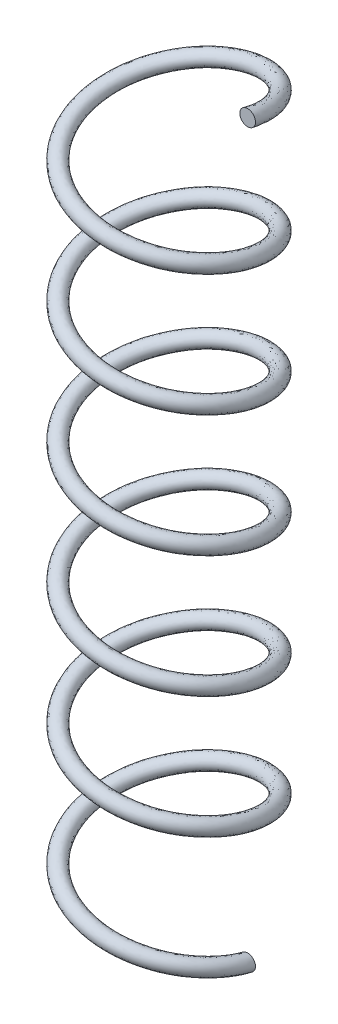
SolidWorks part; units mm, degrees
ref_plane "Front Plane" through (0, 0, 0) normal (0, 0, 1) x (1, 0, 0)
ref_plane "Top Plane" through (0, 0, 0) normal (0, 1, 0) x (1, 0, 0)
ref_plane "Right Plane" through (0, 0, 0) normal (1, 0, 0) x (0, 0, -1)
sketch "Sketch1" plane through (0, 0, 0) normal (1, 0, 0) x (0, 0, -1)
  line L0 (0, 0) -> (0, 19) construction
  dimension "D1" = 19
sketch "Sketch2" plane through (0, 0, 0) normal (0, 1, 0) x (1, 0, 0)
  circle A0 centre (0, 0) radius 2
  dimension "D1" = 4
curve "Helix/Spiral1" pitch 3.1 height 18.6 turns 6
sketch "Sketch3" plane through (0, 0, 0) normal (0, 1, 0) x (1, 0, 0)
  arc A0 (9.9705, 0) -> (5.8804, 2.7912) centre (6.973, 0) cw
sketch "Sketch4" plane through (0, 0, 0) normal (0, 0, 1) x (1, 0, 0)
  circle A0 centre (2, 0) radius 0.2
  spline S0 degree 3 poles (2, 0) (2, 0.0642) (1.8959, 0.1939) (1.451, 0.3875) (0.7853, 0.5813) (0, 0.775) (-0.7853, 0.9688) (-1.451, 1.1625) (-1.8959, 1.3563) (-2.0521, 1.55) (-1.8959, 1.7438) (-1.451, 1.9375) (-0.7853, 2.1313) (0, 2.325) (0.7853, 2.5188) (1.451, 2.7125) (1.8959, 2.9063) (2.0521, 3.1) (1.8959, 3.2938) (1.451, 3.4875) (0.7853, 3.6813) (0, 3.875) (-0.7853, 4.0687) (-1.451, 4.2625) (-1.8959, 4.4562) (-2.0521, 4.65) (-1.8959, 4.8438) (-1.451, 5.0375) (-0.7853, 5.2313) (0, 5.425) (0.7853, 5.6188) (1.451, 5.8125) (1.8959, 6.0063) (2.0521, 6.2) (1.8959, 6.3938) (1.451, 6.5875) (0.7853, 6.7813) (0, 6.975) (-0.7853, 7.1688) (-1.451, 7.3625) (-1.8959, 7.5563) (-2.0521, 7.75) (-1.8959, 7.9438) (-1.451, 8.1375) (-0.7853, 8.3313) (0, 8.525) (0.7853, 8.7188) (1.451, 8.9125) (1.8959, 9.1063) (2.0521, 9.3) (1.8959, 9.4938) (1.451, 9.6875) (0.7853, 9.8813) (0, 10.075) (-0.7853, 10.2687) (-1.451, 10.4625) (-1.8959, 10.6562) (-2.0521, 10.85) (-1.8959, 11.0437) (-1.451, 11.2375) (-0.7853, 11.4312) (0, 11.625) (0.7853, 11.8187) (1.451, 12.0125) (1.8959, 12.2062) (2.0521, 12.4) (1.8959, 12.5937) (1.451, 12.7875) (0.7853, 12.9812) (0, 13.175) (-0.7853, 13.3687) (-1.451, 13.5625) (-1.8959, 13.7562) (-2.0521, 13.95) (-1.8959, 14.1437) (-1.451, 14.3375) (-0.7853, 14.5312) (0, 14.725) (0.7853, 14.9187) (1.451, 15.1125) (1.8959, 15.3062) (2.0521, 15.5) (1.8959, 15.6937) (1.451, 15.8875) (0.7853, 16.0812) (0, 16.275) (-0.7853, 16.4687) (-1.451, 16.6625) (-1.8959, 16.8562) (-2.0521, 17.05) (-1.8959, 17.2437) (-1.451, 17.4375) (-0.7853, 17.6312) (0, 17.825) (0.7853, 18.0187) (1.451, 18.2125) (1.8959, 18.4061) (2, 18.5358) (2, 18.6) knots 0 0 0 0 0.010417 0.020833 0.03125 0.041667 0.052083 0.0625 0.072917 0.083333 0.09375 0.104167 0.114583 0.125 0.135417 0.145833 0.15625 0.166667 0.177083 0.1875 0.197917 0.208333 0.21875 0.229167 0.239583 0.25 0.260417 0.270833 0.28125 0.291667 0.302083 0.3125 0.322917 0.333333 0.34375 0.354167 0.364583 0.375 0.385417 0.395833 0.40625 0.416667 0.427083 0.4375 0.447917 0.458333 0.46875 0.479167 0.489583 0.5 0.510417 0.520833 0.53125 0.541667 0.552083 0.5625 0.572917 0.583333 0.59375 0.604167 0.614583 0.625 0.635417 0.645833 0.65625 0.666667 0.677083 0.6875 0.697917 0.708333 0.71875 0.729167 0.739583 0.75 0.760417 0.770833 0.78125 0.791667 0.802083 0.8125 0.822917 0.833333 0.84375 0.854167 0.864583 0.875 0.885417 0.895833 0.90625 0.916667 0.927083 0.9375 0.947917 0.958333 0.96875 0.979167 0.989583 1 1 1 1 construction
  dimension "D1" = 0.4
sweep "Sweep1" add profiles "Sketch4" path "Helix/Spiral1"
equation "\"spring height\"= 19"
equation "\"D3@Helix/Spiral1\"      = \"height spring@Sketch1\""
equation "\"spring revolutions\"= 6"
equation "\"D5@Helix/Spiral1\"=\"spring revolutions\""
equation "\"D1@Sketch1\"=\"spring height\""
